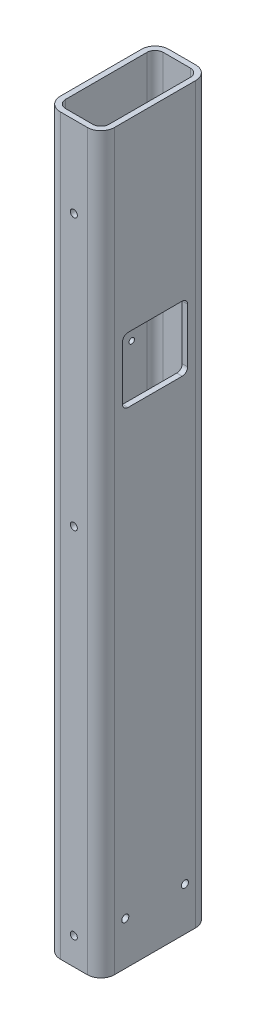
SolidWorks part; units mm, degrees
ref_plane "Front Plane" through (0, 0, 0) normal (0, 0, 1) x (1, 0, 0)
ref_plane "Top Plane" through (0, 0, 0) normal (0, 1, 0) x (1, 0, 0)
ref_plane "Right Plane" through (0, 0, 0) normal (1, 0, 0) x (0, 0, -1)
sketch "Sketch1" plane through (0, 0, 0) normal (0, 0, 1) x (1, 0, 0)
  line L0 (0, -338.5) -> (0, 338.5)
  point P4 (0, 0)
  dimension "D1" = 677
other "Rhs c350 as 100X50X5.0 RHS C350(1)"
ref_plane "Plane1" through (0, -338.5, 0) normal (0, 1, 0) x (-1, 0, 0)
sketch "Sketch11" plane through (0, -338.5, 0) normal (0, 1, 0) x (-1, 0, 0)
  line L0 (-12.5, 45) -> (12.5, 45)
  line L1 (-12.5, -50) -> (12.5, -50)
  line L2 (-25, -37.5) -> (-25, 37.5)
  line L3 (-12.5, 50) -> (12.5, 50)
  line L4 (25, -37.5) -> (25, 37.5)
  line L5 (-25, -50) -> (25, 50) construction
  line L6 (-25, 50) -> (25, -50) construction
  line L7 (20, -37.5) -> (20, 37.5)
  line L8 (-12.5, -45) -> (12.5, -45)
  line L9 (-20, -37.5) -> (-20, 37.5)
  arc A0 (-25, 37.5) -> (-12.5, 50) centre (-12.5, 37.5) cw
  arc A1 (12.5, 50) -> (25, 37.5) centre (12.5, 37.5) cw
  arc A2 (-12.5, -50) -> (-25, -37.5) centre (-12.5, -37.5) cw
  arc A3 (12.5, -50) -> (25, -37.5) centre (12.5, -37.5) ccw
  arc A4 (-20, 37.5) -> (-12.5, 45) centre (-12.5, 37.5) cw
  arc A5 (12.5, 45) -> (20, 37.5) centre (12.5, 37.5) cw
  arc A6 (12.5, -45) -> (20, -37.5) centre (12.5, -37.5) ccw
  arc A7 (-12.5, -45) -> (-20, -37.5) centre (-12.5, -37.5) cw
  point P0 (0, 0)
  point P30 (-25, 0)
  point P31 (0, 50)
  point P32 (25, 0)
  point P33 (0, -50)
  point P34 (0, 0)
  dimension "D2" = 12.5
  dimension "Thickness" = 5
  dimension "Width" = 50
  dimension "Depth" = 100
sketch "Sketch12" plane through (25, 0, 0) normal (1, 0, 0) x (0, 0, -1)
  line L0 (-37.5, 338.5) -> (37.5, 338.5) construction
  line L1 (-14.8492, 123.6508) -> (14.8492, 123.6508) construction
  line L2 (-14.8492, 123.6508) -> (-14.8492, 153.3492) construction
  line L3 (-14.8492, 153.3492) -> (14.8492, 153.3492) construction
  line L4 (14.8492, 123.6508) -> (14.8492, 153.3492) construction
  line L5 (-14.8492, 123.6508) -> (14.8492, 153.3492) construction
  line L6 (-14.8492, 153.3492) -> (14.8492, 123.6508) construction
  line L7 (0, 338.5) -> (0, 138.5) construction
  circle A0 centre (14.8492, 153.3492) radius 2.25
  circle A1 centre (-14.8492, 153.3492) radius 2.25
  circle A2 centre (-14.8492, 123.6508) radius 2.25
  circle A3 centre (14.8492, 123.6508) radius 2.25
  point P0 (0, 138.5)
  dimension "D2" = 4.5
  dimension "D1" = 42
  dimension "D3" = 200
extrude "Cut-Extrude1" cut sketch "Sketch12" against normal blind 10
sketch "Sketch13" plane through (0, 0, -50) normal (0, 0, 1) x (1, 0, 0)
  line L0 (22.5, 125.9008) -> (22.5, 151.0992) construction
  line L1 (25, 125.9008) -> (20, 125.9008) construction
  line L2 (20, 151.0992) -> (25, 151.0992) construction
  line L3 (22.5, 138.5) -> (0, 138.5) construction
  line L4 (0, 138.5) -> (0, 338.5) construction
  line L5 (-12.5, 338.5) -> (12.5, 338.5) construction
  circle A0 centre (0, 263.5) radius 4 construction
  circle A1 centre (0, 13.5) radius 4 construction
  dimension "D1" = 8
  dimension "D2" = 250
sketch "Sketch16" plane through (25, 0, 0) normal (1, 0, 0) x (0, 0, -1)
  line L0 (-14.8492, 123.6508) -> (14.8492, 153.3492) construction
  line L1 (-25, 108.5) -> (25, 108.5)
  line L2 (-30, 113.5) -> (-30, 163.5)
  line L3 (-25, 168.5) -> (25, 168.5)
  line L4 (30, 113.5) -> (30, 163.5)
  line L5 (-30, 108.5) -> (30, 168.5) construction
  line L6 (-30, 168.5) -> (30, 108.5) construction
  arc A1 (-25, 108.5) -> (-30, 113.5) centre (-25, 113.5) cw
  arc A2 (25, 108.5) -> (30, 113.5) centre (25, 113.5) ccw
  arc A3 (25, 168.5) -> (30, 163.5) centre (25, 163.5) cw
  arc A4 (-30, 163.5) -> (-25, 168.5) centre (-25, 163.5) cw
  point P0 (0, 138.5)
  point P6 (0, 138.5)
  dimension "D2" = 5
  dimension "D1" = 60
extrude "Cut-Extrude2" cut sketch "Sketch16" against normal blind 10
sketch "Sketch17" plane through (-20, 0, 0) normal (1, 0, 0) x (0, 0, -1)
  line L0 (0, 138.5) -> (30, 138.5) construction
  line L1 (30, 113.5) -> (30, 163.5) construction
  line L2 (0, 138.5) -> (0, 108.5) construction
  line L3 (-25, 108.5) -> (25, 108.5) construction
  line L5 (-23.5, 115) -> (23.5, 115) construction
  line L6 (-23.5, 115) -> (-23.5, 162) construction
  line L7 (-23.5, 162) -> (23.5, 162) construction
  line L8 (23.5, 115) -> (23.5, 162) construction
  line L9 (-23.5, 115) -> (23.5, 162) construction
  line L10 (-23.5, 162) -> (23.5, 115) construction
  circle A0 centre (0, 138.5) radius 12.5
  circle A1 centre (-23.5, 162) radius 2.5
  circle A2 centre (23.5, 162) radius 2.5
  circle A3 centre (-23.5, 115) radius 2.5
  circle A4 centre (23.5, 115) radius 2.5
  dimension "D1" = 25
  dimension "D3" = 5
  dimension "D2" = 47
extrude "Cut-Extrude3" cut sketch "Sketch17" against normal blind 10
sketch "Sketch18" plane through (0, 0, -50) normal (0, 0, -1) x (-1, 0, 0)
  circle A0 centre (0, 263.5) radius 3.25
  circle A1 centre (0, 13.5) radius 3.25
  dimension "D1" = 6.5
extrude "Cut-Extrude4" cut sketch "Sketch18" against normal through all
sketch "Sketch19" plane through (0, 0, -50) normal (0, 0, -1) x (-1, 0, 0)
  line L0 (0, -338.5) -> (0, -313.5) construction
  line L1 (-12.5, -338.5) -> (12.5, -338.5) construction
  circle A0 centre (0, -313.5) radius 3.25
  dimension "D1" = 6.5
  dimension "D2" = 25
extrude "Cut-Extrude5" cut sketch "Sketch19" against normal through all
sketch "Sketch20" plane through (25, 0, 0) normal (1, 0, 0) x (0, 0, -1)
  line L0 (-27.5, -298.5) -> (27.5, -298.5) construction
  line L1 (0, -338.5) -> (0, -298.5) construction
  line L2 (-37.5, -338.5) -> (37.5, -338.5) construction
  circle A0 centre (27.5, -298.5) radius 3.25
  circle A1 centre (-27.5, -298.5) radius 3.25
  point P3 (0, -298.5)
  dimension "D3" = 6.5
  dimension "D1" = 55
  dimension "D2" = 40
extrude "Cut-Extrude6" cut sketch "Sketch20" against normal through all
sketch "Sketch21" plane through (-20, 0, 0) normal (1, 0, 0) x (0, 0, -1)
  line L0 (0, 138.5) -> (0, 160.5) construction
  circle A0 centre (0, 138.5) radius 22 construction
  circle A1 centre (0, 160.5) radius 2.25
  circle A2 centre (22, 138.5) radius 2.25
  circle A3 centre (0, 116.5) radius 2.25
  circle A4 centre (-22, 138.5) radius 2.25
  point P5 (0, 0)
  point P6 (0, 0)
  point P14 (0, 138.5)
  dimension "D1" = 44
  dimension "D2" = 4.5
  dimension "D3" = 4
extrude "Cut-Extrude7" cut sketch "Sketch21" against normal blind 10
